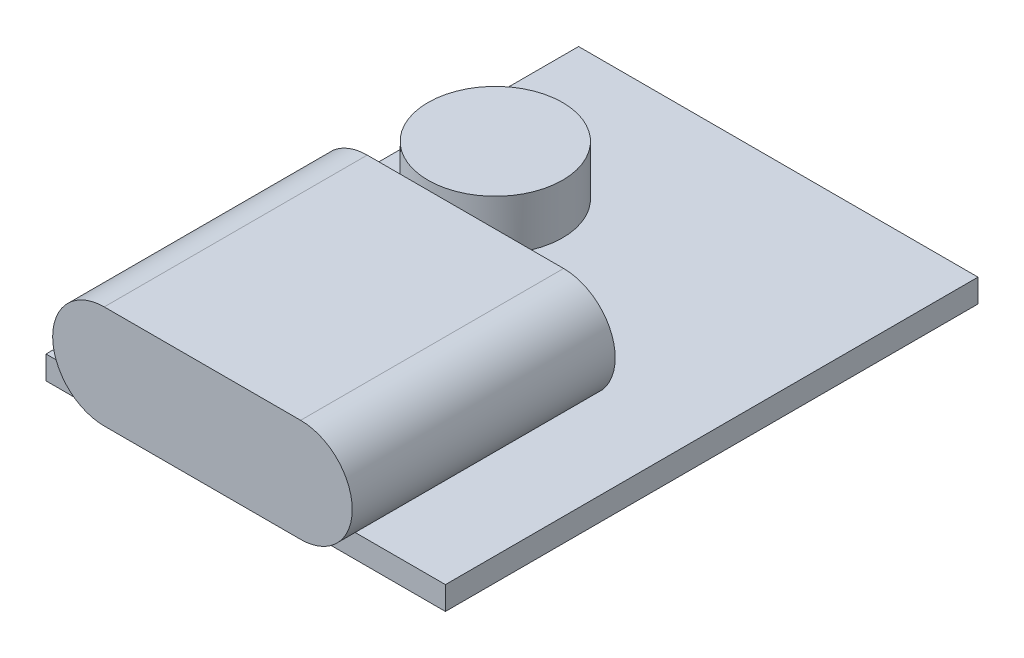
SolidWorks part; units mm, degrees
ref_plane "Спереди" through (0, 0, 0) normal (0, 0, 1) x (1, 0, 0)
ref_plane "Сверху" through (0, 0, 0) normal (0, 1, 0) x (1, 0, 0)
ref_plane "Справа" through (0, 0, 0) normal (1, 0, 0) x (0, 0, -1)
sketch "Эскиз1" plane through (0, 0, 0) normal (0, 1, 0) x (1, 0, 0)
  line L0 (0, 16) -> (0, 0) construction
  line L1 (-6, 0) -> (6, 0)
  line L2 (-6, 0) -> (-6, 16)
  line L3 (-6, 16) -> (6, 16)
  line L4 (6, 0) -> (6, 16)
  point P6 (0, -2)
  dimension "D1" = 12
  dimension "D2" = 16
  dimension "D3" = 2
extrude "Бобышка-Вытянуть1" add sketch "Эскиз1" along normal blind 0.7
sketch "Эскиз2" plane through (0, 0, 0) normal (0, 0, 1) x (1, 0, 0)
  line L0 (-2.95, 2.55) -> (2.95, 2.55) construction
  line L1 (-2.95, 4.1) -> (2.95, 4.1)
  line L2 (-2.95, 1) -> (2.95, 1)
  line L3 (0, 2.55) -> (0, 0) construction
  line L4 (-6, 0) -> (6, 0) construction
  line L5 (-4.5, 2.55) -> (4.5, 2.55) construction
  arc A0 (-2.95, 4.1) -> (-2.95, 1) centre (-2.95, 2.55) ccw
  arc A1 (2.95, 1) -> (2.95, 4.1) centre (2.95, 2.55) ccw
  point P2 (0, 2.55)
  point P11 (0, 1)
  point P12 (4.5, 2.55)
  point P15 (-4.5, 2.55)
  dimension "D1" = 3.1
  dimension "D2" = 9
  dimension "D3" = 4.1
extrude "Бобышка-Вытянуть2" add sketch "Эскиз2" against normal blind 7.9 from offset 1.3
sketch "Эскиз3" plane through (0, 0, 0) normal (0, 1, 0) x (1, 0, 0)
  circle A0 centre (-3.2834, 10.7819) radius 2.0226
extrude "Бобышка-Вытянуть3" add sketch "Эскиз3" along normal blind 2.2
ref_plane "Плоскость1" through (0, 0, 2) normal (0, 0, 1) x (1, 0, 0)
sketch "Эскиз4" [suppressed] plane through (0, 0, 0) normal (0, 1, 0) x (1, 0, 0)
  line L0 (3, 10) -> (3, 7) construction
  line L1 (5, 10) -> (1, 10) construction
  line L2 (1, 7) -> (5, 7) construction
  line L3 (-3, 10) -> (-3, 7) construction
  line L4 (-1, 10) -> (-5, 10) construction
  line L5 (-5, 7) -> (-1, 7) construction
  line L6 (0, -50) -> (0, 50) construction
  circle A0 centre (3, 8.5) radius 0.75
  circle A1 centre (-3, 8.5) radius 0.75
  dimension "D1" = 1.5
extrude "Бобышка-Вытянуть4" [suppressed] add sketch "Эскиз4" along normal blind 3
